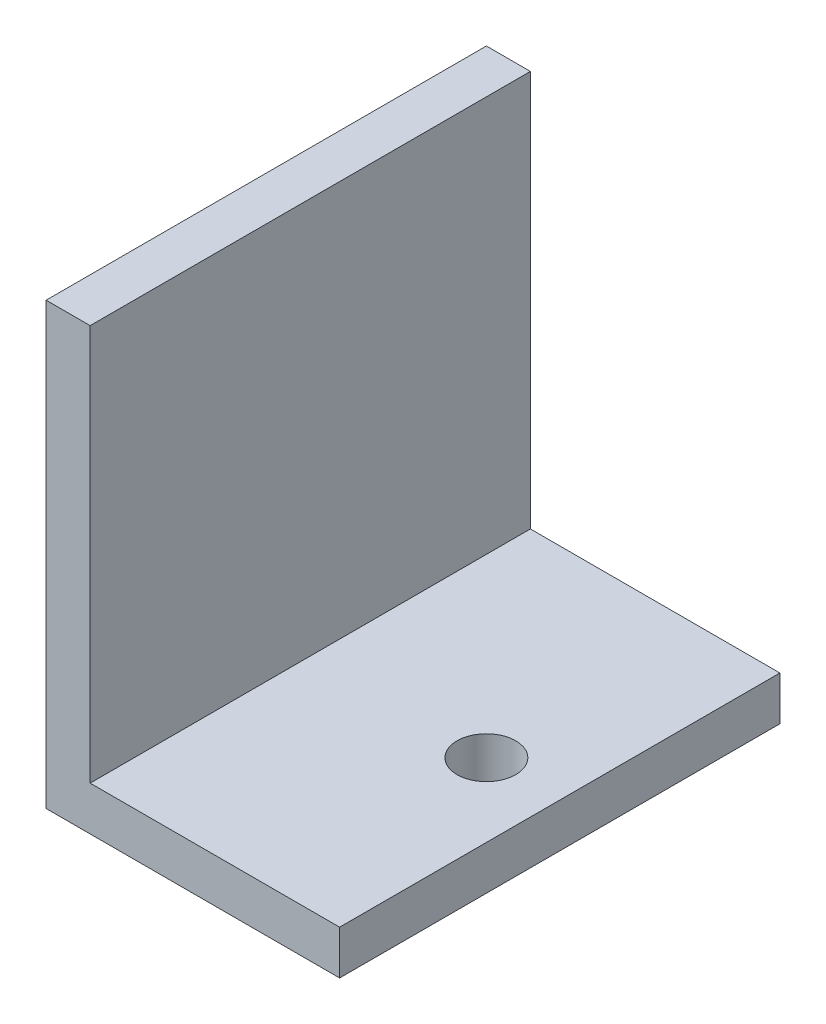
SolidWorks part; units mm, degrees
material "1023 Carbon Steel Sheet (SS)"
ref_plane "Front Plane" through (0, 0, 0) normal (1, 0, 0) x (0, 1, 0)
ref_plane "Top Plane" through (0, 0, 0) normal (0, 0, 1) x (0, 1, 0)
ref_plane "Right Plane" through (0, 0, 0) normal (0, 1, 0) x (-1, 0, 0)
sketch "Sketch1" plane through (0, 0, 0) normal (0, 0, 1) x (0, 1, 0)
  line L0 (0, 0) -> (-30, 0)
  line L1 (-30, 0) -> (-30, -30)
  line L2 (-30, -30) -> (-27, -30)
  line L3 (-27, -30) -> (-27, -3)
  line L4 (-27, -3) -> (0, -3)
  line L5 (0, -3) -> (0, 0)
  dimension "D1" = 30
  dimension "D2" = 30
  dimension "D3" = 3
  dimension "D4" = 3
extrude "Boss-Extrude1" add sketch "Sketch1" along normal blind 30
sketch "Sketch2" plane through (0, -27, 0) normal (0, 1, 0) x (-1, 0, 0)
  line L0 (0, 30) -> (0, 0) construction
  line L1 (-30, 0) -> (-3, 0) construction
  circle A0 centre (-15, 15) radius 2
  dimension "D2" = 4
  dimension "D1" = 15
  dimension "D3" = 15
extrude "Cut-Extrude1" cut sketch "Sketch2" against normal blind 30
sketch "Sketch3" plane through (0, -27, 0) normal (0, 1, 0) x (-1, 0, 0)
  line L0 (-30, 0) -> (-3, 0) construction
  line L1 (-30, 30) -> (-20, 30)
  line L2 (-30, 30) -> (-30, 0)
  line L3 (-30, 0) -> (-20, 0)
  line L4 (-20, 30) -> (-20, 0)
  dimension "D1" = 10
extrude "Cut-Extrude2" cut sketch "Sketch3" against normal blind 6
